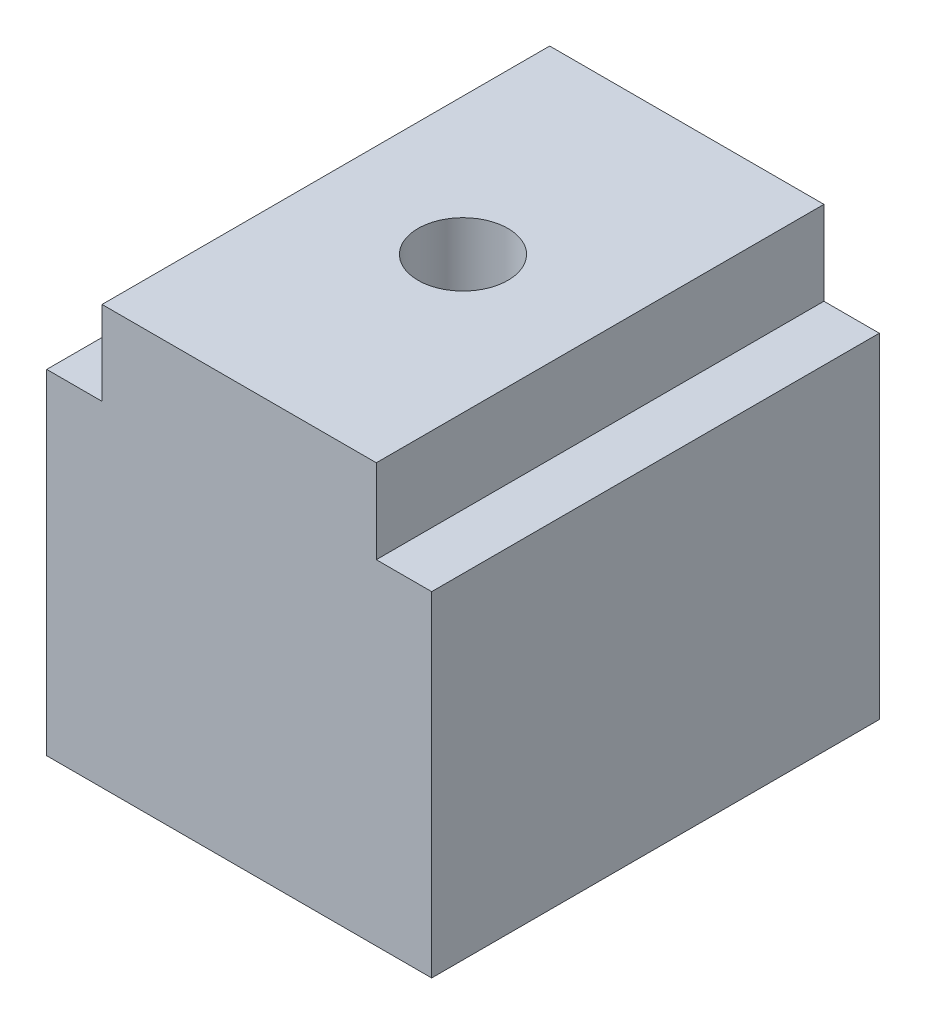
SolidWorks part; units mm, degrees
ref_plane "Front Plane" through (0, 0, 0) normal (0, 0, 1) x (1, 0, 0)
ref_plane "Top Plane" through (0, 0, 0) normal (0, 1, 0) x (1, 0, 0)
ref_plane "Right Plane" through (0, 0, 0) normal (1, 0, 0) x (0, 0, -1)
sketch "Sketch1" plane through (0, 0, 0) normal (0, 1, 0) x (1, 0, 0)
  line L1 (-10.922, -12.7) -> (10.922, -12.7)
  line L2 (-10.922, -12.7) -> (-10.922, 12.7)
  line L3 (-10.922, 12.7) -> (10.922, 12.7)
  line L4 (10.922, -12.7) -> (10.922, 12.7)
  line L5 (-10.922, -12.7) -> (10.922, 12.7) construction
  line L6 (-10.922, 12.7) -> (10.922, -12.7) construction
  point P0 (0, 0)
  dimension "D1" = 21.844
  dimension "D2" = 25.4
extrude "Boss-Extrude1" add sketch "Sketch1" along normal blind 23.749
sketch "Bolt Hole Pattern" plane through (0, 23.749, 0) normal (0, 1, 0) x (1, 0, 0)
  point P0 (0, 0)
hole_wizard "Clearance Hole for Alignment Pin" positions "Sketch3" profile "Sketch4" hole size "#10" standard "ANSI Inch" end condition through all
sketch "Sketch3" plane through (0, 23.749, 0) normal (0, 1, 0) x (1, 0, 0)
  point P0 (0, 0)
sketch "Sketch4" plane through (0, 23.749, 0) normal (1, 0, 0) x (0, 0, 1)
  line L0 (0, 0) -> (0, 23.749)
  line L1 (0, 23.749) -> (2.5527, 23.749)
  line L2 (2.5527, 23.749) -> (2.5527, 0)
  line L5 (2.5527, 0) -> (0, 0)
  line L11 (0, -6.35) -> (0, 107.95) construction
  dimension "Thru Hole Dia." = 5.1054
  dimension "Thru Hole Depth" = 23.749
sketch "Sketch6" plane through (0, 23.749, 0) normal (0, 1, 0) x (1, 0, 0)
  line L0 (-10.922, -12.7) -> (10.922, -12.7) construction
  line L1 (10.922, 12.7) -> (7.7811, 12.7)
  line L2 (10.922, 12.7) -> (10.922, -12.7)
  line L3 (10.922, -12.7) -> (7.7811, -12.7)
  line L4 (7.7811, 12.7) -> (7.7811, -12.7)
  line L5 (0, 12.7) -> (0, -12.7) construction
  line L6 (10.922, 12.7) -> (-10.922, 12.7) construction
  line L7 (-7.7811, 12.7) -> (-7.7811, -12.7)
  line L8 (-10.922, -12.7) -> (-7.7811, -12.7)
  line L9 (-10.922, 12.7) -> (-10.922, -12.7)
  line L10 (-10.922, 12.7) -> (-7.7811, 12.7)
extrude "Clearance Rabbit" cut sketch "Sketch6" against normal blind 4.7625
